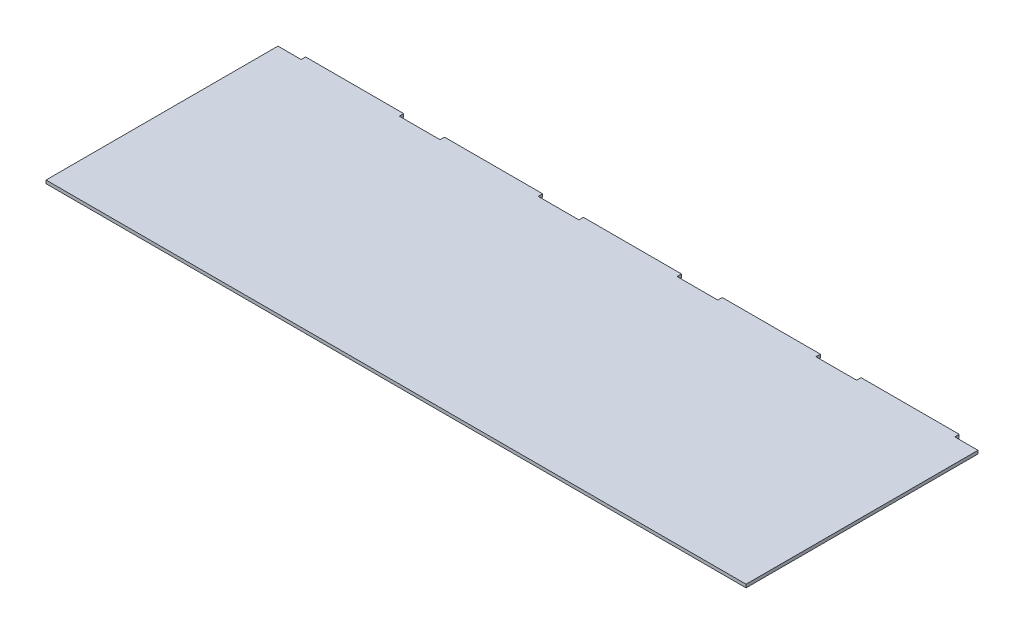
SolidWorks part; units mm, degrees
material "6061-T6 (SS)"
ref_plane "X-Y Datum" through (0, 0, 0) normal (0, 0, 1) x (1, 0, 0)
ref_plane "X-Z Datum" through (0, 0, 0) normal (0, 1, 0) x (1, 0, 0)
ref_plane "Y-Z Datum" through (0, 0, 0) normal (1, 0, 0) x (0, 0, -1)
sketch "Sketch1" plane through (0, 0, 0) normal (0, 1, 0) x (1, 0, 0)
  line L1 (-249.174, 82.55) -> (249.174, 82.55)
  line L2 (-249.174, 82.55) -> (-249.174, -82.55)
  line L3 (-249.174, -82.55) -> (249.174, -82.55)
  line L4 (249.174, 82.55) -> (249.174, -82.55)
  line L5 (-249.174, 82.55) -> (249.174, -82.55) construction
  line L6 (-249.174, -82.55) -> (249.174, 82.55) construction
  point P0 (0, 0)
  dimension "D1" = 498.348
  dimension "D2" = 165.1
extrude "Boss-Extrude1" add sketch "Sketch1" along normal mid plane 2.286
sketch "Sketch2" plane through (0, 0, -82.55) normal (0, 0, -1) x (-1, 0, 0)
  line L24 (-232.6386, -1.143) -> (-232.6386, 1.143)
  line L25 (-232.6386, 1.143) -> (-162.7886, 1.143)
  line L26 (-162.7886, -1.143) -> (-232.6386, -1.143)
  line L27 (-162.7886, 1.143) -> (-162.7886, -1.143)
extrude "Boss-Extrude2" add sketch "Sketch2" along normal blind 3.175
pattern_linear "LPattern1" count 5 spacing 98.8568 along (-1, 0, 0) of "Boss-Extrude2"
